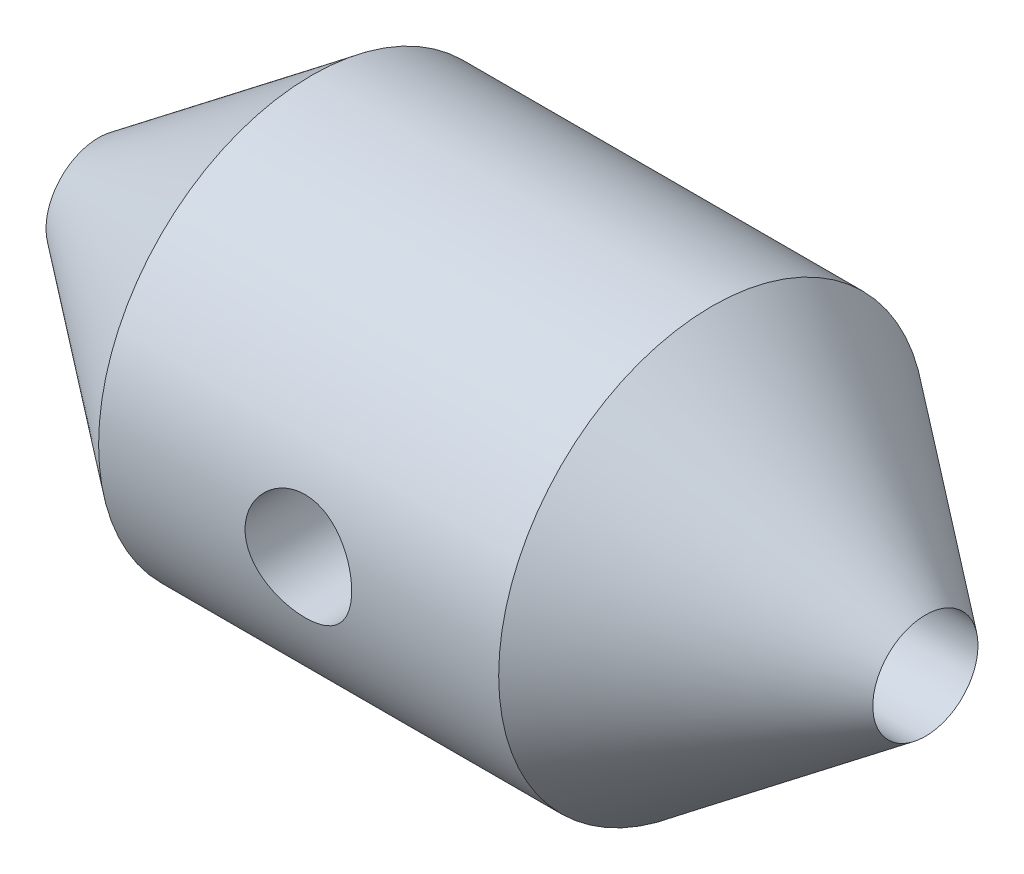
SolidWorks part; units mm, degrees
ref_plane "Front Plane" through (0, 0, 0) normal (0, 0, 1) x (1, 0, 0)
ref_plane "Top Plane" through (0, 0, 0) normal (0, 1, 0) x (1, 0, 0)
ref_plane "Right Plane" through (0, 0, 0) normal (1, 0, 0) x (0, 0, -1)
sketch "Sketch1" plane through (0, 0, 0) normal (1, 0, 0) x (0, 0, -1)
  circle A0 centre (0, 0) radius 101.6
  circle A1 centre (0, 0) radius 25.4
  dimension "D1" = 203.2
  dimension "D2" = 50.8
extrude "Boss-Extrude1" add sketch "Sketch1" along normal blind 190.5
sketch "Sketch2" plane through (190.5, 0, 0) normal (1, 0, 0) x (0, 0, -1)
  circle A1 centre (0, 0) radius 101.6
  circle A2 centre (0, 0) radius 101.6
  dimension "D1" = 0
extrude "Boss-Extrude2" add sketch "Sketch2" along normal blind 101.6 draft 37
sketch "Sketch3" plane through (0, 0, 0) normal (-1, 0, 0) x (0, 0, 1)
  circle A1 centre (0, 0) radius 101.6
  circle A2 centre (0, 0) radius 101.6
  dimension "D1" = 0
extrude "Boss-Extrude3" add sketch "Sketch3" along normal blind 101.6 draft 37
sketch "Sketch4" plane through (-101.6, 0, 0) normal (-1, 0, 0) x (0, 0, 1)
  circle A1 centre (0, 0) radius 25.0389
  circle A2 centre (0, 0) radius 25.0389
  dimension "D1" = 0
extrude "Cut-Extrude1" cut sketch "Sketch4" against normal blind 453.39
ref_plane "Plane1" through (0, 0, 254) normal (0, 0, 1) x (1, 0, 0)
sketch "Sketch5" plane through (0, 0, 254) normal (0, 0, 1) x (1, 0, 0)
  line L0 (-120.9219, 0) -> (311.1529, 0) construction
  circle A0 centre (95.1155, 0) radius 25.4
  dimension "D1" = 50.8
extrude "Cut-Extrude3" cut sketch "Sketch5" against normal blind 351.79
